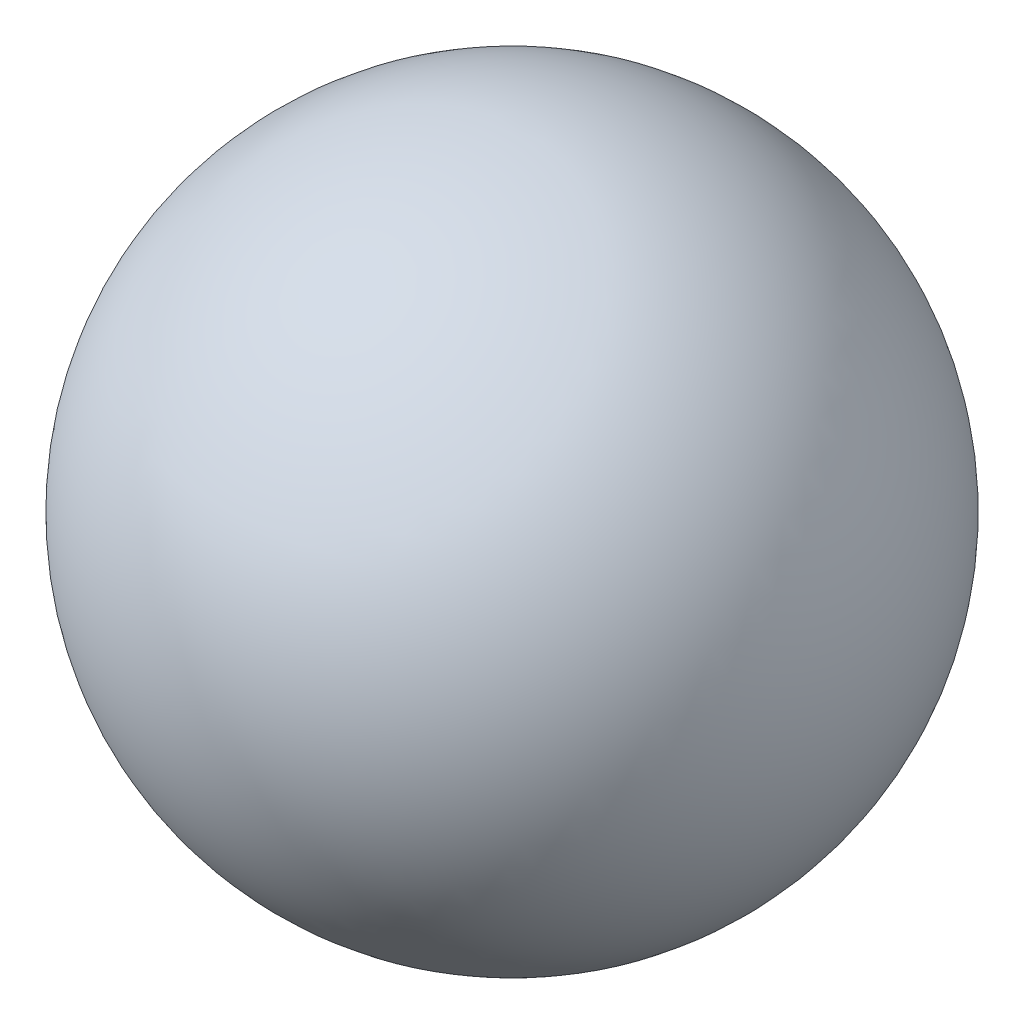
SolidWorks part; units mm, degrees
ref_plane "Front Plane" through (0, 0, 0) normal (0, 0, 1) x (1, 0, 0)
ref_plane "Top Plane" through (0, 0, 0) normal (0, 1, 0) x (1, 0, 0)
ref_plane "Right Plane" through (0, 0, 0) normal (1, 0, 0) x (0, 0, -1)
sketch "Sketch1" plane through (0, 0, 0) normal (0, 0, 1) x (1, 0, 0)
  line L0 (0, 4.7625) -> (0, -4.7625)
  arc A0 (0, 4.7625) -> (0, -4.7625) centre (0, 0) cw
  dimension "D1" = 4.7625
revolve "Revolve5" add sketch "Sketch1" angle 360 about L0
equation "\"plate_diam\"= 4"
equation "\"magnet_thickness\"= 0.125"
equation "\"coupling_diam\"= 2.5"
equation "\"ball_diam\"= .375"
equation "\"dowel_diam\"= 0.25"
equation "\"plate_thickness\"= 0.47"
equation "\"magnet_diam\"=1.26"
equation "\"glue_thickness\"= 0.005"
equation "\"magnet_radial_tol\"= 0.0025"
equation "\"dowel_length\"= .75"
equation "\"dowel_center_to_center\" = 2 * ( sqr ( ( ( ( \"dowel_diam\" + \"ball_diam\" ) / 2 ) ^ 2 ) / 2 ) )"
equation "\"dowel_slot_width\"= \"dowel_center_to_center\" + \"dowel_diam\""
equation "\"dowel_slot_depth\" = \"dowel_diam\" * 0.75"
equation "\"corner_relief_diam\"= 0.25"
equation "\"central_hole_diam\"= 0.5"
equation "\"ball_center_to_slot_bottom\"= ( \"dowel_center_to_center\" / 2 ) + ( \"dowel_diam\" / 2 )"
equation "\"total_coupling_height\"= 1"
equation "\"ball_embed_depth\"= 0.15"
equation "\"ball_hole_diam\"= 2 * sqr ( ( \"ball_diam\" / 2 ) ^ 2 + - ( \"ball_diam\" / 2 - \"ball_embed_depth\" ) ^ 2 )"
equation "\"total_stack_height\"= \"plate_thickness\" - \"dowel_slot_depth\" + \"ball_center_to_slot_bottom\" + ( \"ball_diam\" / 2 ) - \"ball_embed_depth\" + \"plate_thickness\""
equation "\"D1@Sketch1\"=\"ball_diam\"/2"
